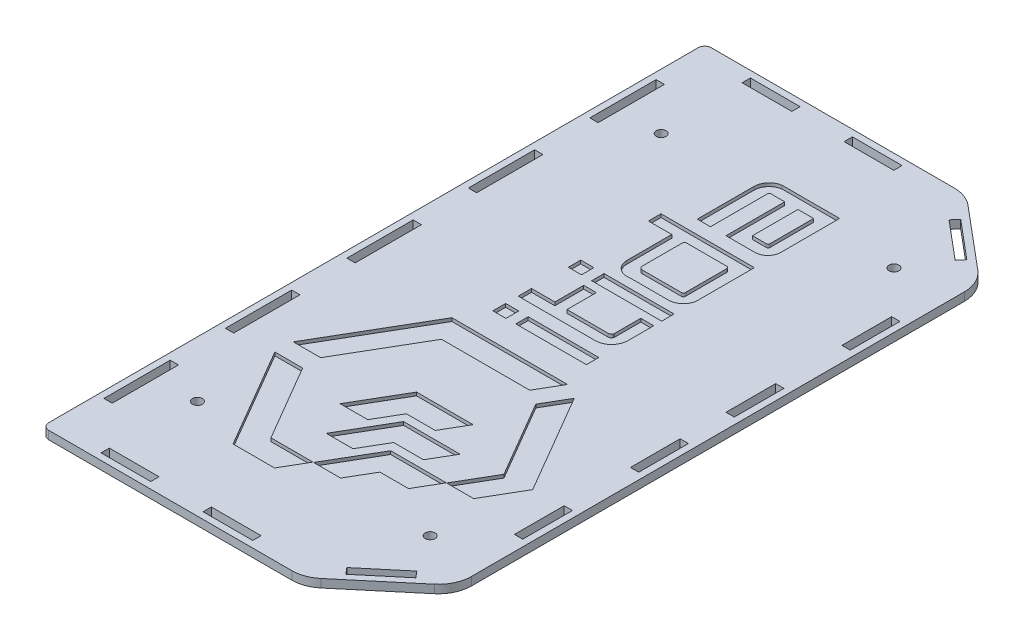
SolidWorks part; units mm, degrees
material "Maple"
ref_plane "Front Plane" through (0, 0, 0) normal (0, 0, 1) x (1, 0, 0)
ref_plane "Top Plane" through (0, 0, 0) normal (0, 1, 0) x (1, 0, 0)
ref_plane "Right Plane" through (0, 0, 0) normal (1, 0, 0) x (0, 0, -1)
sketch "Sketch1" plane through (0, 0, 0) normal (0, 1, 0) x (1, 0, 0)
  line L1 (52, -100) -> (-52, -100) construction
  line L2 (52, -100) -> (52, 100) construction
  line L3 (52, 100) -> (-52, 100) construction
  line L4 (-52, -100) -> (-52, 100) construction
  line L5 (52, -100) -> (-52, 100) construction
  line L6 (52, 100) -> (-52, -100) construction
  line L12 (-36.21, -96.75) -> (-52, -96.75) construction
  line L13 (-36.21, -98) -> (-21.21, -98)
  line L14 (-36.21, -98) -> (-36.21, -95.5)
  line L15 (-36.21, -95.5) -> (-21.21, -95.5)
  line L16 (-21.21, -98) -> (-21.21, -95.5)
  line L17 (-36.21, -98) -> (-21.21, -95.5) construction
  line L18 (-36.21, -95.5) -> (-21.21, -98) construction
  line L19 (-5.42, -98) -> (9.58, -98)
  line L20 (-5.42, -98) -> (-5.42, -95.5)
  line L21 (-5.42, -95.5) -> (9.58, -95.5)
  line L22 (9.58, -98) -> (9.58, -95.5)
  line L23 (-5.42, -98) -> (9.58, -95.5) construction
  line L24 (-5.42, -95.5) -> (9.58, -98) construction
  line L29 (-52, -100) -> (27, -100)
  line L30 (27, -100) -> (52, -79.0225)
  line L31 (-21.21, -96.75) -> (-5.42, -96.75) construction
  line L32 (9.58, -96.75) -> (25.37, -96.75) construction
  line L33 (52, -79.0225) -> (52, 79.0225)
  line L34 (-52, -100) -> (-52, 100)
  line L35 (-28.71, 0) -> (22.6314, 0) construction
  line L36 (-36.21, 98) -> (-36.21, 95.5)
  line L37 (-36.21, 98) -> (-21.21, 98)
  line L38 (-21.21, 98) -> (-21.21, 95.5)
  line L39 (-36.21, 95.5) -> (-21.21, 95.5)
  line L40 (-5.42, 98) -> (-5.42, 95.5)
  line L41 (-5.42, 98) -> (9.58, 98)
  line L42 (9.58, 98) -> (9.58, 95.5)
  line L43 (-5.42, 95.5) -> (9.58, 95.5)
  line L44 (27, 100) -> (52, 79.0225)
  line L45 (-52, 100) -> (27, 100)
  line L46 (30.8621, -90.885) -> (32.4691, -92.8001)
  line L47 (32.4691, -92.8001) -> (43.9598, -83.1583)
  line L48 (43.9598, -83.1583) -> (42.3528, -81.2431)
  line L49 (42.3528, -81.2431) -> (30.8621, -90.885)
  line L50 (38.2144, -87.9792) -> (39.5, -89.5113) construction
  line L52 (30.8621, -90.885) -> (25.37, -95.4934)
  line L53 (25.37, -95.4934) -> (9.58, -95.5)
  line L54 (42.3528, -81.2431) -> (47.5, -76.9241) construction
  line L55 (47.5, -76.9241) -> (47.5, -67.3903) construction
  line L56 (47.5, 21.9241) -> (50, 21.9241)
  line L57 (50, -56.9241) -> (47.5, -56.9241)
  line L58 (50, -56.9241) -> (50, -41.9241)
  line L59 (50, -41.9241) -> (47.5, -41.9241)
  line L60 (47.5, -56.9241) -> (47.5, -41.9241)
  line L61 (50, -56.9241) -> (47.5, -41.9241) construction
  line L62 (50, -41.9241) -> (47.5, -56.9241) construction
  line L63 (47.5, -21.9241) -> (50, -21.9241)
  line L64 (47.5, -21.9241) -> (47.5, -6.9241)
  line L65 (47.5, -6.9241) -> (50, -6.9241)
  line L66 (50, -21.9241) -> (50, -6.9241)
  line L67 (47.5, -21.9241) -> (50, -6.9241) construction
  line L68 (47.5, -6.9241) -> (50, -21.9241) construction
  line L69 (50, 21.9241) -> (50, 6.9241)
  line L70 (47.5, 6.9241) -> (50, 6.9241)
  line L71 (47.5, 21.9241) -> (47.5, 6.9241)
  line L72 (50, 56.9241) -> (47.5, 56.9241)
  line L73 (50, 56.9241) -> (50, 41.9241)
  line L74 (50, 41.9241) -> (47.5, 41.9241)
  line L75 (47.5, 56.9241) -> (47.5, 41.9241)
  line L76 (42.3528, 81.2431) -> (30.8621, 90.885)
  line L77 (43.9598, 83.1583) -> (42.3528, 81.2431)
  line L78 (32.4691, 92.8001) -> (43.9598, 83.1583)
  line L79 (30.8621, 90.885) -> (32.4691, 92.8001)
  line L80 (-50, -46.6667) -> (-50, -26.6667)
  line L81 (-50, -83.3333) -> (-47.5, -83.3333)
  line L82 (-50, -83.3333) -> (-50, -63.3333)
  line L83 (-50, -63.3333) -> (-47.5, -63.3333)
  line L84 (-47.5, -83.3333) -> (-47.5, -63.3333)
  line L85 (-50, -83.3333) -> (-47.5, -63.3333) construction
  line L86 (-50, -63.3333) -> (-47.5, -83.3333) construction
  line L87 (-50, -46.6667) -> (-47.5, -46.6667)
  line L88 (-47.5, -46.6667) -> (-47.5, -26.6667)
  line L89 (-50, -26.6667) -> (-47.5, -26.6667)
  line L90 (-50, -10) -> (-50, 10)
  line L91 (-50, -10) -> (-47.5, -10)
  line L92 (-47.5, -10) -> (-47.5, 10)
  line L93 (-50, 10) -> (-47.5, 10)
  line L94 (-50, 26.6667) -> (-50, 46.6667)
  line L95 (-50, 26.6667) -> (-47.5, 26.6667)
  line L96 (-47.5, 26.6667) -> (-47.5, 46.6667)
  line L97 (-50, 46.6667) -> (-47.5, 46.6667)
  line L98 (-50, 63.3333) -> (-50, 83.3333)
  line L99 (-50, 63.3333) -> (-47.5, 63.3333)
  line L100 (-47.5, 63.3333) -> (-47.5, 83.3333)
  line L101 (-50, 83.3333) -> (-47.5, 83.3333)
  line L102 (-48.75, -83.3333) -> (-48.75, -100) construction
  line L103 (-48.75, -63.3333) -> (-48.75, -46.6667) construction
  line L104 (-48.75, 83.3333) -> (-48.75, 100) construction
  line L105 (0, -27.01) -> (0, 32.9312) construction
  line L106 (-29.6967, -27.01) -> (44.7033, -27.01) construction
  circle A4 centre (35.1272, -70) radius 1.5 construction
  circle A5 centre (35.1272, -70) radius 1.5
  circle A6 centre (35.1272, 70) radius 1.5 construction
  circle A7 centre (35.1272, 70) radius 1.5
  circle A8 centre (-35.1272, 70) radius 1.5
  circle A9 centre (-35.1272, -70) radius 1.5
  point P0 (0, 0)
  point P6 (2.08, -96.75)
  point P12 (-28.71, -96.75)
  point P37 (52, 0)
  point P38 (-52, 0)
  point P40 (39.5, -89.5113)
  point P45 (48.75, -49.4241)
  point P53 (48.75, -14.4241)
  point P70 (-48.75, -73.3333)
  dimension "D1" = 104
  dimension "D2" = 200
  dimension "D3" = 2.5
  dimension "D4" = 2
  dimension "D5" = 15
  dimension "D6" = 15.79
  dimension "D7" = 130
  dimension "D8" = 25
  dimension "D9" = 2
  dimension "D10" = 4.5
  dimension "D11" = 15
  dimension "D12" = 20
  dimension "D13" = 20
  dimension "D14" = 2.5
  dimension "D15" = 2
  dimension "D16" = 20
  dimension "D17" = 2.5
  dimension "D18" = 2
  dimension "D19" = 5
extrude "Boss-Extrude1" add sketch "Sketch1" along normal mid plane 2.5
fillet "Fillet1" radius 10 4 edges at (52, 0, -79.0225) (27, 0, -100) (27, 0, 100) (52, 0, 79.0225)
fillet "Fillet2" radius 2 2 edges at (-52, 0, 100) (-52, 0, -100)
sketch "Sketch2" plane through (0, 1.25, 0) normal (0, 1, 0) x (1, 0, 0)
  line L160 (-36.338, -45.404) -> (-18.6114, -75.7645)
  line L161 (-18.6114, -75.7645) -> (-6.0755, -75.7645)
  line L162 (-6.0755, -75.7645) -> (6.7542, -53.7286) construction
  line L163 (6.7542, -53.7286) -> (31.9885, -53.7286) construction
  line L164 (31.9885, -53.7286) -> (38.5472, -42.4638)
  line L165 (38.5472, -42.4638) -> (20.9464, -12.3188)
  line L166 (20.9464, -12.3188) -> (16.6765, -19.6526)
  line L167 (16.6765, -19.6526) -> (30.1875, -42.7931)
  line L168 (30.1454, -42.721) -> (19.5401, -60.9363) construction
  line L169 (19.5401, -60.9363) -> (10.912, -60.9363)
  line L170 (10.912, -60.9363) -> (6.5507, -68.4269)
  line L171 (6.5507, -68.4269) -> (-14.5091, -68.4269) construction
  line L172 (-14.5091, -68.4269) -> (-27.9515, -45.404)
  line L173 (-27.9515, -45.404) -> (-36.338, -45.404)
  line L174 (-27.9515, -39.9761) -> (-14.5181, -16.9254)
  line L175 (-14.5181, -16.9254) -> (12.1142, -16.9254)
  line L176 (12.1142, -16.9254) -> (16.3126, -9.7213)
  line L177 (16.3126, -9.7213) -> (-18.5836, -9.7213)
  line L178 (-18.5836, -9.7213) -> (-36.2154, -39.9761)
  line L179 (-36.2154, -39.9761) -> (-27.9515, -39.9761)
  line L180 (-7.3183, -58.9005) -> (1.2703, -44.1631)
  line L181 (1.2703, -44.1631) -> (18.3241, -44.1631)
  line L182 (18.3241, -44.1631) -> (14.2587, -51.139)
  line L183 (14.2587, -51.139) -> (5.2477, -51.139)
  line L184 (5.2477, -51.139) -> (0.7245, -58.9005)
  line L185 (0.7245, -58.9005) -> (-7.3183, -58.9005)
  line L186 (-4.6393, -49.0773) -> (-0.3369, -41.6947)
  line L187 (-0.3369, -41.6947) -> (8.3733, -41.6947)
  line L188 (8.3733, -41.6947) -> (12.572, -34.4901)
  line L189 (12.572, -34.4901) -> (-4.486, -34.4901)
  line L190 (-4.486, -34.4901) -> (-12.9871, -49.0773)
  line L191 (-12.9871, -49.0773) -> (-4.6393, -49.0773)
  line L192 (-14.201, 5.9225) -> (-14.201, 9.9315)
  line L193 (-7.3183, -1.6905) -> (-7.3183, 2.0541)
  line L194 (-7.3183, -1.6905) -> (13.9799, -1.6905)
  line L195 (13.9799, -1.6905) -> (13.9799, 2.0541)
  line L196 (-7.3183, 2.0541) -> (13.9799, 2.0541)
  line L197 (-14.201, -1.7428) -> (-14.201, 2.1152)
  line L198 (-14.201, -1.7428) -> (-10.2467, -1.7428)
  line L199 (-10.2467, -1.7428) -> (-10.2467, 2.1152)
  line L200 (-14.201, 2.1152) -> (-10.2467, 2.1152)
  line L201 (-7.1637, 21.0414) -> (-7.1637, 24.7861)
  line L202 (-7.1637, 21.0414) -> (13.9799, 21.0414)
  line L203 (13.9799, 21.0414) -> (13.9799, 24.7861)
  line L204 (-7.1637, 24.7861) -> (13.9799, 24.7861)
  line L205 (-14.201, 21.0414) -> (-14.201, 24.7861)
  line L206 (-14.201, 21.0414) -> (-10.2467, 21.0414)
  line L207 (-10.2467, 21.0414) -> (-10.2467, 24.7861)
  line L208 (-14.201, 24.7861) -> (-10.2467, 24.7861)
  line L209 (-14.201, 9.9315) -> (-7.1637, 9.9315)
  line L210 (-7.1637, 9.9315) -> (-7.1637, 18.6334)
  line L211 (-7.1637, 18.6334) -> (-3.3438, 18.6334)
  line L212 (-3.3438, 18.6334) -> (-3.3438, 9.7909)
  line L213 (-3.3438, 9.7909) -> (9.016, 9.7909)
  line L214 (-14.201, 5.9225) -> (9.016, 5.9225)
  line L215 (10.0695, 10.5443) -> (10.0695, 18.6334)
  line L216 (10.0695, 18.6334) -> (13.9799, 18.6334)
  line L217 (13.9799, 18.6334) -> (13.9799, 10.7546)
  line L218 (-14.201, 49.0105) -> (13.9799, 49.0105)
  line L219 (13.9799, 49.0105) -> (13.9799, 31.4922)
  line L220 (-14.201, 49.0105) -> (-14.201, 45.2171)
  line L221 (-14.201, 45.2171) -> (-7.1637, 45.2171)
  line L222 (-7.1637, 45.2171) -> (-7.1637, 31.7021)
  line L223 (-3.3438, 44.4585) -> (-3.3438, 32.2509)
  line L224 (10.0695, 32.2509) -> (10.0695, 44.4585)
  line L225 (-2.3073, 45.2171) -> (9.4793, 45.2171)
  line L226 (-2.3073, 31.4922) -> (9.4793, 31.4922)
  line L227 (-2.1526, 27.564) -> (9.5019, 27.564)
  line L228 (-3.3438, 70.1841) -> (-3.3438, 53.0797)
  line L229 (-3.3438, 53.0797) -> (-7.3183, 53.0797)
  line L230 (-7.3183, 53.0797) -> (-7.3183, 70.1841)
  line L231 (-2.3073, 70.8048) -> (1.3409, 70.8048)
  line L232 (1.3409, 70.8048) -> (1.3409, 53.0797)
  line L233 (1.3409, 53.0797) -> (10.0695, 53.0797)
  line L234 (10.0695, 57.7696) -> (10.0695, 70.8048)
  line L235 (10.0695, 70.8048) -> (5.3411, 70.8048)
  line L236 (5.3411, 70.8048) -> (5.3411, 57.0799)
  line L237 (5.3411, 57.0799) -> (9.4793, 57.0799)
  line L238 (-3.3438, 74.7361) -> (13.9799, 74.7361)
  line L239 (13.9799, 74.7361) -> (13.9799, 57.0799)
  line L240 (-6.0755, -75.7645) -> (-1.8034, -68.4269)
  line L241 (-1.8034, -68.4269) -> (-14.5091, -68.4269)
  line L242 (6.5507, -68.4269) -> (-1.6179, -68.4269)
  line L243 (-1.6179, -68.4269) -> (6.9397, -53.7286)
  line L244 (6.9397, -53.7286) -> (23.7365, -53.7286)
  line L245 (23.7365, -53.7286) -> (19.5401, -60.9363)
  line L246 (31.9885, -53.7286) -> (23.8206, -53.7286)
  line L247 (23.8206, -53.7286) -> (30.1875, -42.7931)
  arc A24 (9.016, 9.7909) -> (10.0695, 10.5443) centre (9.016, 10.9041) ccw
  arc A25 (9.016, 5.9225) -> (13.9799, 10.7546) centre (9.016, 10.8882) ccw
  arc A26 (10.0695, 53.0797) -> (13.9799, 57.0799) centre (10.0695, 56.9911) ccw
  arc A27 (9.4793, 57.0799) -> (10.0695, 57.7696) centre (9.4793, 57.6772) ccw
  arc A28 (-3.3438, 70.1841) -> (-2.3073, 70.8048) centre (-2.6396, 70.1841) cw
  arc A29 (-7.1637, 31.7021) -> (-2.1526, 27.564) centre (-2.9495, 31.7021) ccw
  arc A30 (9.5019, 27.564) -> (13.9799, 31.4922) centre (9.5019, 32.0804) ccw
  arc A31 (9.4793, 31.4922) -> (10.0695, 32.2509) centre (9.4793, 32.1011) ccw
  arc A32 (-2.3073, 31.4922) -> (-3.3438, 32.2509) centre (-2.3073, 32.5795) cw
  arc A33 (-3.3438, 44.4585) -> (-2.3073, 45.2171) centre (-2.5479, 44.4585) cw
  arc A34 (9.4793, 45.2171) -> (10.0695, 44.4585) centre (9.4793, 44.6083) cw
  arc A35 (-7.3183, 70.1841) -> (-3.3438, 74.7361) centre (-2.7244, 70.1841) cw
extrude "Cut-Extrude2" cut sketch "Sketch2" against normal blind 1 contours L227 A30 L219 L218 L220 L221 L222 A29 L225 A34 L224 A31 L226 A32 L223 A33 | A35 L230 L229 L228 A28 L231 L232 L233 A26 L239 L238 A27 L237 L236 L235 L234 | L204 L201 L202 L203 | L208 L205 L206 L207 | L214 A25 L217 L216 L215 A24 L213 L212 L211 L210 L209 L192 | L200 L197 L198 L199 | L196 L193 L194 L195 | L178 L179 L174 L175 L176 L177 | L190 L191 L186 L187 L188 L189 | L185 L184 L183 L182 L181 L180 | L245 L244 L243 L242 L170 L169 | L247 L246 L164 L165 L166 L167 | L240 L241 L172 L173 L160 L161
